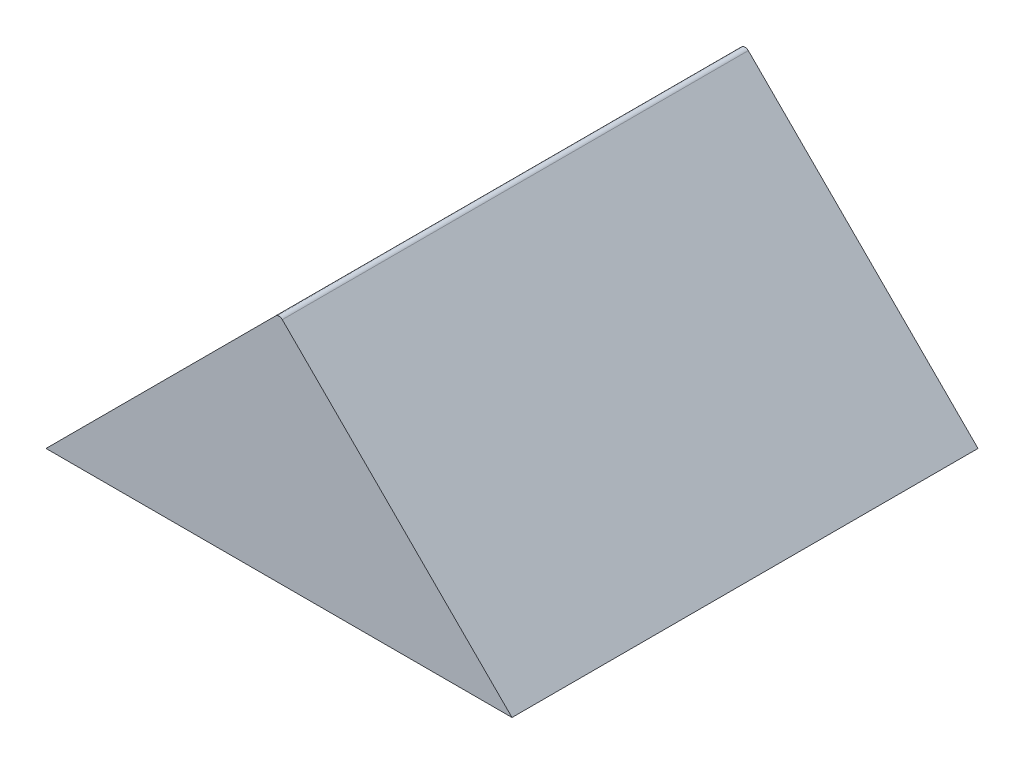
SolidWorks part; units mm, degrees
ref_plane "Front Plane" through (0, 0, 0) normal (0, 0, 1) x (1, 0, 0)
ref_plane "Top Plane" through (0, 0, 0) normal (0, 1, 0) x (1, 0, 0)
ref_plane "Right Plane" through (0, 0, 0) normal (1, 0, 0) x (0, 0, -1)
sketch "Sketch1" plane through (0, 0, 0) normal (0, 1, 0) x (1, 0, 0)
  line L1 (-10, 10) -> (10, 10)
  line L2 (-10, 10) -> (-10, -10)
  line L3 (-10, -10) -> (10, -10)
  line L4 (10, 10) -> (10, -10)
  dimension "D1" = 20
  dimension "D2" = 20
  dimension "D3" = 10
  dimension "D4" = 10
extrude "Boss-Extrude1" add sketch "Sketch1" along normal blind 10
sketch "Sketch2" plane through (0, 0, 10) normal (0, 0, 1) x (1, 0, 0)
  line L0 (-10, 10) -> (-10, 0)
  line L1 (-10, 0) -> (0, 10)
  line L2 (-10, 10) -> (10, 10) construction
  line L3 (0, 10) -> (-10, 10)
extrude "Cut-Extrude1" cut sketch "Sketch2" against normal blind 20
sketch "Sketch3" plane through (0, 0, 10) normal (0, 0, 1) x (1, 0, 0)
  line L0 (0, 10) -> (10, 10)
  line L1 (10, 10) -> (10, 0)
  line L2 (10, 0) -> (0, 10)
extrude "Cut-Extrude3" cut sketch "Sketch3" against normal blind 20
fillet "Fillet1" radius 0.2 1 edges at (0, 10, 0)
